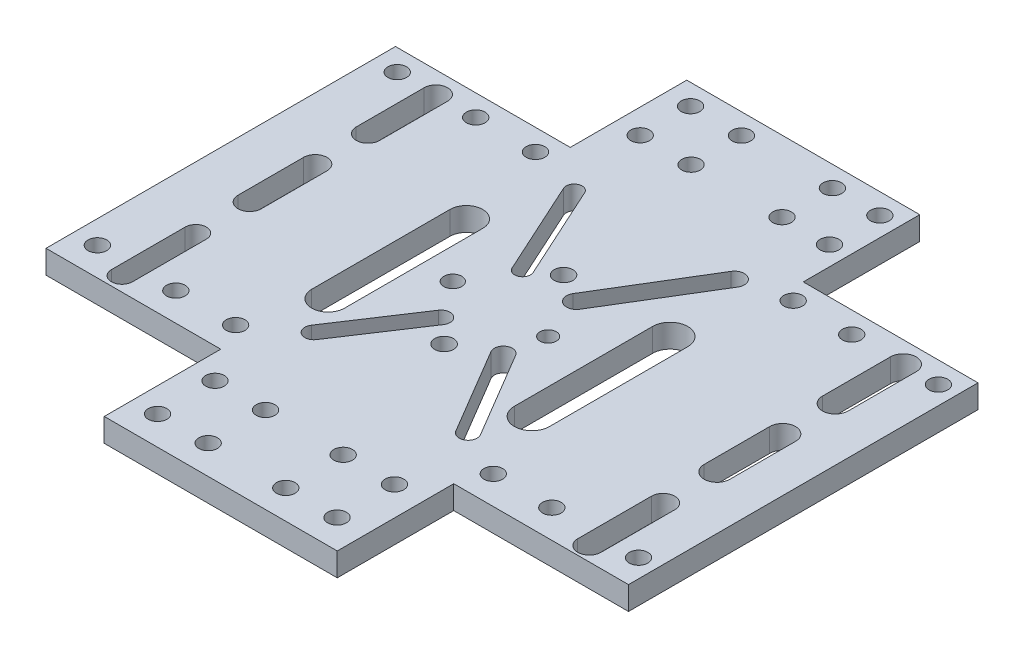
SolidWorks part; units mm, degrees
ref_plane "前视基准面" through (0, 0, 0) normal (0, 0, 1) x (1, 0, 0)
ref_plane "上视基准面" through (0, 0, 0) normal (0, 1, 0) x (1, 0, 0)
ref_plane "右视基准面" through (0, 0, 0) normal (1, 0, 0) x (0, 0, -1)
sketch "草图1" plane through (0, 0, 0) normal (0, 1, 0) x (1, 0, 0)
  line L0 (0, -50) -> (75, -50)
  line L1 (75, 0) -> (175, 0)
  line L2 (0, -50) -> (0, -200)
  line L3 (75, -250) -> (175, -250)
  line L4 (250, -50) -> (250, -200)
  line L5 (75, -50) -> (75, 0)
  line L6 (75, 0) -> (175, 0)
  line L7 (175, 0) -> (175, -50)
  line L8 (175, -50) -> (250, -50)
  line L9 (250, -50) -> (250, -200)
  line L10 (250, -200) -> (175, -200)
  line L11 (175, -200) -> (175, -250)
  line L12 (175, -250) -> (75, -250)
  line L13 (75, -250) -> (75, -200)
  line L14 (75, -200) -> (0, -200)
  line L15 (26.4942, -110.938) -> (26.4942, -139.0911) construction
  line L16 (31.5215, -110.938) -> (31.5215, -139.0911)
  line L17 (21.4668, -110.938) -> (21.4668, -139.0911)
  line L18 (26.4942, -59.1564) -> (26.4942, -88.315) construction
  line L19 (31.5215, -59.1564) -> (31.5215, -88.315)
  line L20 (21.4668, -59.1564) -> (21.4668, -88.315)
  line L21 (26.4942, -193.8891) -> (26.4942, -162.2169) construction
  line L22 (21.9696, -193.8891) -> (21.9696, -162.2169)
  line L23 (31.0188, -193.8891) -> (31.0188, -162.2169)
  line L24 (227.085, -59.1564) -> (227.085, -88.315) construction
  line L25 (232.6151, -59.1564) -> (232.6151, -88.315)
  line L26 (221.5549, -59.1564) -> (221.5549, -88.315)
  line L27 (227.085, -110.938) -> (227.085, -139.0911) construction
  line L28 (232.6151, -110.938) -> (232.6151, -139.0911)
  line L29 (221.5549, -110.938) -> (221.5549, -139.0911)
  line L30 (227.085, -162.2169) -> (227.085, -193.8891) construction
  line L31 (232.1124, -162.2169) -> (232.1124, -193.8891)
  line L32 (222.0577, -162.2169) -> (222.0577, -193.8891)
  line L33 (79.2812, -98.8724) -> (79.2812, -158.195) construction
  line L34 (86.3195, -98.8724) -> (86.3195, -158.195)
  line L35 (72.243, -98.8724) -> (72.243, -158.195)
  line L36 (166.7569, -98.8724) -> (166.7569, -158.195) construction
  line L37 (174.298, -98.8724) -> (174.298, -158.195)
  line L38 (159.2159, -98.8724) -> (159.2159, -158.195)
  line L39 (91.8496, -65.1892) -> (110.4507, -105.9107) construction
  line L40 (94.9512, -63.7724) -> (113.5524, -104.4939)
  line L41 (88.748, -66.606) -> (107.3491, -107.3275)
  line L42 (159.2159, -63.7724) -> (133.5765, -105.9107) construction
  line L43 (162.8519, -65.9848) -> (137.2125, -108.123)
  line L44 (155.58, -61.5601) -> (129.9405, -103.6983)
  line L45 (88.748, -173.7798) -> (110.4507, -140.9224) construction
  line L46 (85.5151, -171.6444) -> (107.2179, -138.7871)
  line L47 (91.9808, -175.9151) -> (113.6836, -143.0577)
  line L48 (137.2125, -140.9224) -> (159.2159, -178.053) construction
  line L49 (140.5336, -138.9543) -> (162.537, -176.0849)
  line L50 (133.8914, -142.8905) -> (155.8948, -180.0211)
  arc A0 (31.5215, -110.938) -> (21.4668, -110.938) centre (26.4942, -110.938) ccw
  arc A1 (21.4668, -139.0911) -> (31.5215, -139.0911) centre (26.4942, -139.0911) ccw
  arc A2 (31.5215, -59.1564) -> (21.4668, -59.1564) centre (26.4942, -59.1564) ccw
  arc A3 (21.4668, -88.315) -> (31.5215, -88.315) centre (26.4942, -88.315) ccw
  arc A4 (21.9696, -193.8891) -> (31.0188, -193.8891) centre (26.4942, -193.8891) ccw
  arc A5 (31.0188, -162.2169) -> (21.9696, -162.2169) centre (26.4942, -162.2169) ccw
  arc A6 (232.6151, -59.1564) -> (221.5549, -59.1564) centre (227.085, -59.1564) ccw
  arc A7 (221.5549, -88.315) -> (232.6151, -88.315) centre (227.085, -88.315) ccw
  arc A8 (232.6151, -110.938) -> (221.5549, -110.938) centre (227.085, -110.938) ccw
  arc A9 (221.5549, -139.0911) -> (232.6151, -139.0911) centre (227.085, -139.0911) ccw
  arc A10 (232.1124, -162.2169) -> (222.0577, -162.2169) centre (227.085, -162.2169) ccw
  arc A11 (222.0577, -193.8891) -> (232.1124, -193.8891) centre (227.085, -193.8891) ccw
  arc A12 (86.3195, -98.8724) -> (72.243, -98.8724) centre (79.2812, -98.8724) ccw
  arc A13 (72.243, -158.195) -> (86.3195, -158.195) centre (79.2812, -158.195) ccw
  arc A14 (174.298, -98.8724) -> (159.2159, -98.8724) centre (166.7569, -98.8724) ccw
  arc A15 (159.2159, -158.195) -> (174.298, -158.195) centre (166.7569, -158.195) ccw
  arc A16 (94.9512, -63.7724) -> (88.748, -66.606) centre (91.8496, -65.1892) ccw
  arc A17 (107.3491, -107.3275) -> (113.5524, -104.4939) centre (110.4507, -105.9107) ccw
  arc A18 (162.8519, -65.9848) -> (155.58, -61.5601) centre (159.2159, -63.7724) ccw
  arc A19 (129.9405, -103.6983) -> (137.2125, -108.123) centre (133.5765, -105.9107) ccw
  arc A20 (85.5151, -171.6444) -> (91.9808, -175.9151) centre (88.748, -173.7798) ccw
  arc A21 (113.6836, -143.0577) -> (107.2179, -138.7871) centre (110.4507, -140.9224) ccw
  arc A22 (140.5336, -138.9543) -> (133.8914, -142.8905) centre (137.2125, -140.9224) ccw
  arc A23 (155.8948, -180.0211) -> (162.537, -176.0849) centre (159.2159, -178.053) ccw
  circle A25 centre (140.5336, -125.0146) radius 3.5191
  circle A26 centre (121.0082, -98.8724) radius 4.0219
  circle A27 centre (121.0082, -150.1513) radius 4.0532
  circle A28 centre (99.5994, -125.0146) radius 3.8457
  circle A29 centre (85.5151, -8.883) radius 4
  circle A30 centre (85.5151, -30.5006) radius 4
  circle A31 centre (107.3491, -8.883) radius 4
  circle A32 centre (107.3491, -30.5006) radius 4
  circle A33 centre (146.3962, -8.883) radius 4
  circle A34 centre (166.7569, -8.883) radius 4
  circle A35 centre (146.3962, -30.5006) radius 4
  circle A36 centre (166.7569, -30.5006) radius 4
  circle A37 centre (85.5151, -237.627) radius 4
  circle A38 centre (85.5151, -212.993) radius 4
  circle A39 centre (107.2179, -212.993) radius 4
  circle A40 centre (107.2179, -237.627) radius 4
  circle A41 centre (162.537, -212.993) radius 4
  circle A42 centre (162.537, -237.627) radius 4
  circle A43 centre (140.5336, -212.993) radius 4
  circle A44 centre (140.5336, -237.627) radius 4
  circle A45 centre (9.904, -59.1564) radius 4
  circle A47 centre (242.167, -59.1564) radius 4
  circle A48 centre (242.167, -187.8563) radius 4
  circle A51 centre (204.9647, -59.1564) radius 4
  circle A52 centre (204.9647, -187.8563) radius 4
  circle A53 centre (9.904, -187.8563) radius 4
  circle A54 centre (43.5871, -59.1564) radius 4
  circle A55 centre (43.5871, -187.8563) radius 4
  circle A56 centre (69.2266, -59.1564) radius 4
  circle A57 centre (69.2266, -187.8563) radius 4
  circle A58 centre (179.828, -59.1564) radius 4
  circle A59 centre (179.828, -187.8563) radius 4
  point P0 (0, -125)
  point P1 (250, -125)
  point P4 (75, -250)
  point P5 (175, -250)
  point P6 (26.4942, -125.0146)
  point P7 (0, -200)
  point P8 (250, -200)
  point P9 (75, 0)
  point P10 (175, 0)
  point P11 (0, -50)
  point P12 (250, -50)
  point P29 (26.4942, -73.7357)
  point P36 (26.4942, -178.053)
  point P45 (227.085, -73.7357)
  point P50 (227.085, -125.0146)
  point P57 (227.085, -178.053)
  point P66 (79.2812, -128.5337)
  point P71 (166.7569, -128.5337)
  point P80 (101.1502, -85.55)
  point P85 (146.3962, -84.8416)
  point P92 (99.5994, -157.3511)
  point P99 (148.2142, -159.4877)
  dimension "D1" = 8
  dimension "D2" = 8
  dimension "D3" = 8
  dimension "D4" = 8
extrude "凸台-拉伸1" add sketch "草图1" along normal blind 10 contours L14 L13 L3 L11 L10 L4 L8 L7 L1 L5 L0 L2 A59 A58 A57 A56 A55 A54 A53 A52 A51 A48 A47 A45 A44 A43 A42 A41 A40 A39 A38
